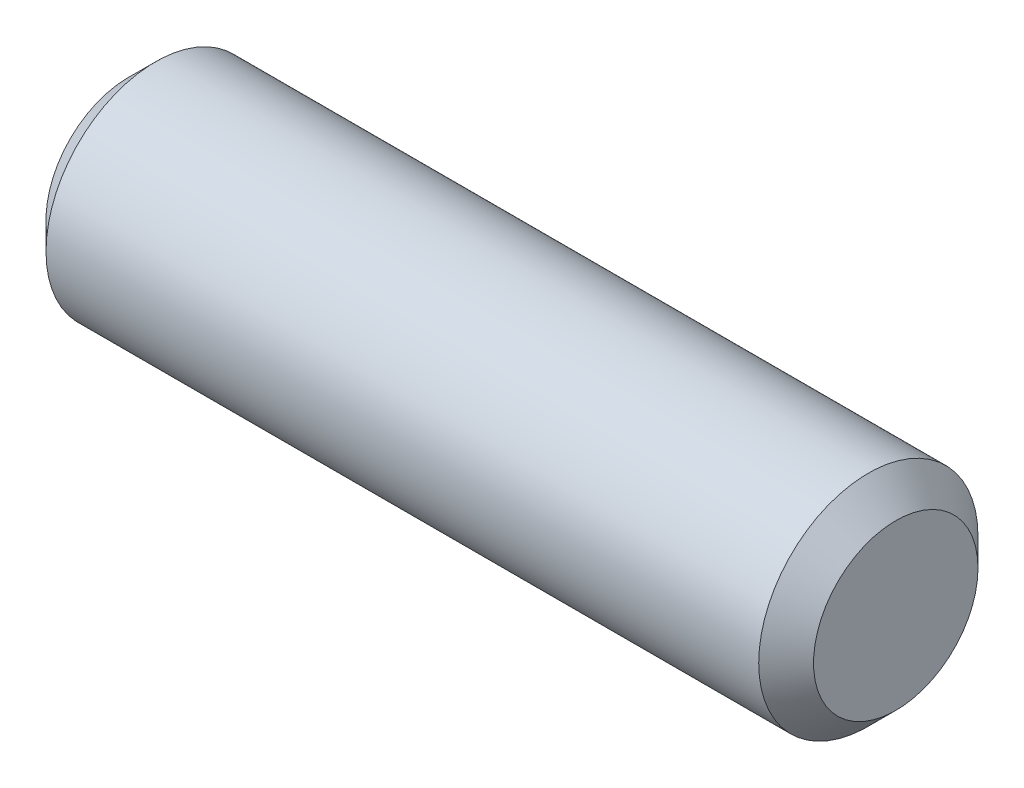
SolidWorks part; units mm, degrees
material "AISI 4340 Aço, normalizado"
ref_plane "Plano frontal" through (0, 0, 0) normal (0, 0, 1) x (1, 0, 0)
ref_plane "Plano superior" through (0, 0, 0) normal (0, 1, 0) x (1, 0, 0)
ref_plane "Plano direito" through (0, 0, 0) normal (1, 0, 0) x (0, 0, -1)
sketch "Esboço1" plane through (0, 0, 0) normal (1, 0, 0) x (0, 0, -1)
  circle A0 centre (0, 0) radius 2
  dimension "D1" = 4
extrude "Ressalto-extrusão1" add sketch "Esboço1" along normal blind 14
chamfer "Chanfro1" distance 0.5 angle 45 2 edges at (14, 0, -2) (0, 0, -2)
